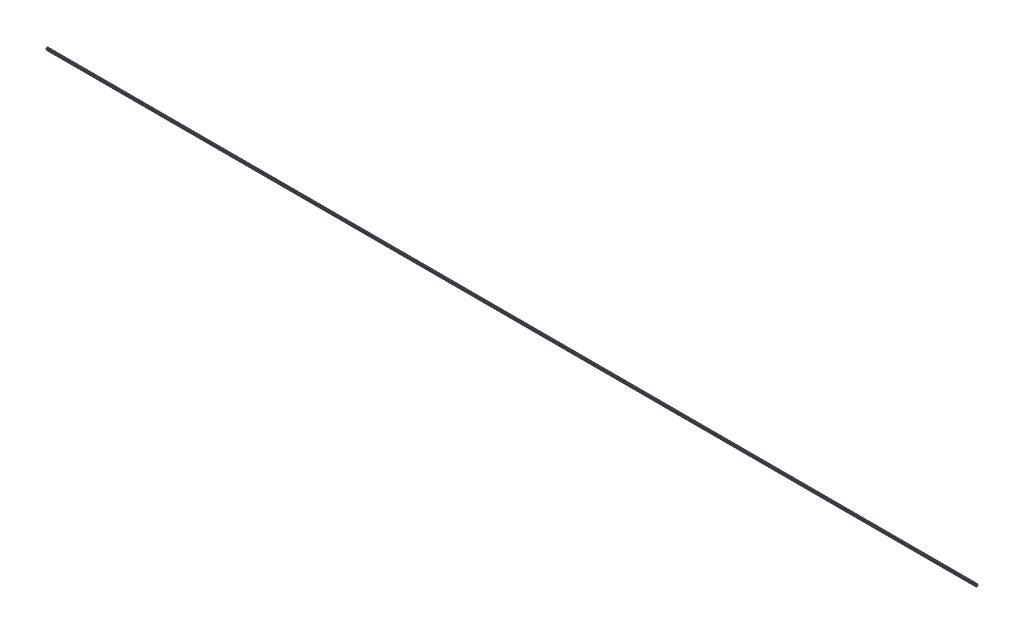
SolidWorks part; units mm, degrees
ref_plane "Front Plane" through (0, 0, 0) normal (0, 0, 1) x (1, 0, 0)
ref_plane "Top Plane" through (0, 0, 0) normal (0, 1, 0) x (1, 0, 0)
ref_plane "Right Plane" through (0, 0, 0) normal (1, 0, 0) x (0, 0, -1)
ref_plane "Plane1" through (0, 0, 0) normal (-1, 0, 0) x (0, -1, 0)
sketch "Sketch1" plane through (0, 0, 0) normal (-1, 0, 0) x (0, -1, 0)
  line L0 (13, -4) -> (13, -8.25)
  line L1 (13, -8.25) -> (9.6642, -8.25)
  line L2 (9.6642, -8.25) -> (6, -4.5858)
  line L3 (6, -4.5858) -> (6, -0.5196)
  line L4 (6, -0.5196) -> (5.7, 0)
  line L5 (5.7, 0) -> (6, 0.5196)
  line L6 (6, 0.5196) -> (6, 4.5858)
  line L7 (6, 4.5858) -> (9.6642, 8.25)
  line L8 (9.6642, 8.25) -> (13, 8.25)
  line L9 (13, 8.25) -> (13, 4)
  line L10 (13, 4) -> (15, 4)
  line L11 (15, 4) -> (15, 13)
  line L12 (13, 15) -> (4, 15)
  line L13 (4, 15) -> (4, 13)
  line L14 (4, 13) -> (8.25, 13)
  line L15 (8.25, 13) -> (8.25, 9.6642)
  line L16 (8.25, 9.6642) -> (4.5858, 6)
  line L17 (4.5858, 6) -> (0.5196, 6)
  line L18 (0.5196, 6) -> (0, 5.7)
  line L19 (0, 5.7) -> (-0.5196, 6)
  line L20 (-0.5196, 6) -> (-4.5858, 6)
  line L21 (-4.5858, 6) -> (-8.25, 9.6642)
  line L22 (-8.25, 9.6642) -> (-8.25, 13)
  line L23 (-8.25, 13) -> (-4, 13)
  line L24 (-4, 13) -> (-4, 15)
  line L25 (-4, 15) -> (-13, 15)
  line L26 (-15, 13) -> (-15, 4)
  line L27 (-15, 4) -> (-13, 4)
  line L28 (-13, 4) -> (-13, 8.25)
  line L29 (-13, 8.25) -> (-9.6642, 8.25)
  line L30 (-9.6642, 8.25) -> (-6, 4.5858)
  line L31 (-6, 4.5858) -> (-6, 0.5196)
  line L32 (-6, 0.5196) -> (-5.7, 0)
  line L33 (-5.7, 0) -> (-6, -0.5196)
  line L34 (-6, -0.5196) -> (-6, -4.5858)
  line L35 (-6, -4.5858) -> (-9.6642, -8.25)
  line L36 (-9.6642, -8.25) -> (-13, -8.25)
  line L37 (-13, -8.25) -> (-13, -4)
  line L38 (-13, -4) -> (-15, -4)
  line L39 (-15, -4) -> (-15, -13)
  line L40 (-13, -15) -> (-4, -15)
  line L41 (-4, -15) -> (-4, -13)
  line L42 (-4, -13) -> (-8.25, -13)
  line L43 (-8.25, -13) -> (-8.25, -9.6642)
  line L44 (-8.25, -9.6642) -> (-4.5858, -6)
  line L45 (-4.5858, -6) -> (-0.5196, -6)
  line L46 (-0.5196, -6) -> (0, -5.7)
  line L47 (0, -5.7) -> (0.5196, -6)
  line L48 (0.5196, -6) -> (4.5858, -6)
  line L49 (4.5858, -6) -> (8.25, -9.6642)
  line L50 (8.25, -9.6642) -> (8.25, -13)
  line L51 (8.25, -13) -> (4, -13)
  line L52 (4, -13) -> (4, -15)
  line L53 (4, -15) -> (13, -15)
  line L54 (15, -13) -> (15, -4)
  line L55 (15, -4) -> (13, -4)
  arc A0 (15, 13) -> (13, 15) centre (13, 13) ccw
  arc A1 (-13, 15) -> (-15, 13) centre (-13, 13) ccw
  arc A2 (-15, -13) -> (-13, -15) centre (-13, -13) ccw
  arc A3 (13, -15) -> (15, -13) centre (13, -13) ccw
  circle A4 centre (0, 0) radius 3.4
  circle A5 centre (11.6, -11.6) radius 2.1
  circle A6 centre (11.6, 11.6) radius 2.1
  circle A7 centre (-11.6, 11.6) radius 2.1
  circle A8 centre (-11.6, -11.6) radius 2.1
extrude "Boss-Extrude1" add sketch "Sketch1" against normal blind 15000
